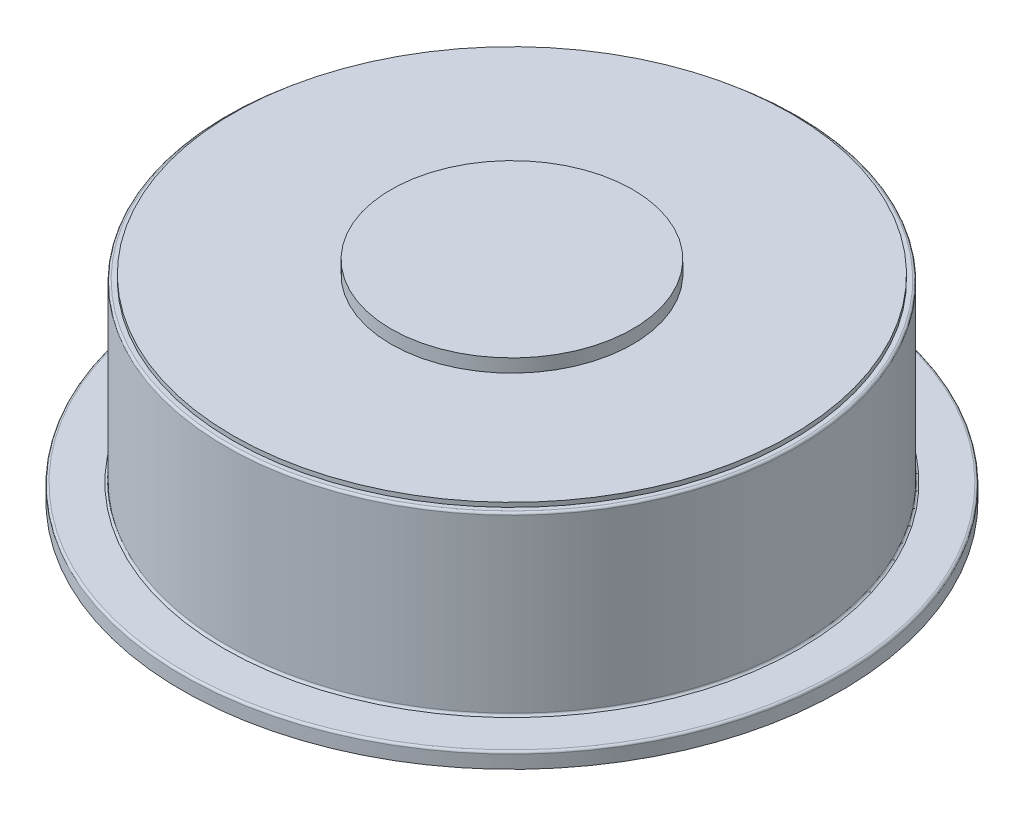
SolidWorks part; units mm, degrees
ref_plane "Ön Düzlem" through (0, 0, 0) normal (0, 0, 1) x (1, 0, 0)
ref_plane "Üst Düzlem" through (0, 0, 0) normal (0, 1, 0) x (1, 0, 0)
ref_plane "Sağ Düzlem" through (0, 0, 0) normal (1, 0, 0) x (0, 0, -1)
sketch "Çizim2" plane through (0, 0, 0) normal (0, 0, 1) x (1, 0, 0)
  line L1 (0, 0) -> (-150, 0)
  line L2 (0, 0) -> (0, 7)
  line L3 (0, 7) -> (-150, 7)
  line L4 (-150, 0) -> (-150, 7)
  line L5 (0, 7) -> (-130, 7)
  line L6 (0, 7) -> (0, 87)
  line L7 (0, 87) -> (-130, 87)
  line L8 (-130, 7) -> (-130, 87)
  dimension "D1" = 7
  dimension "D2" = 80
  dimension "D3" = 150
  dimension "D4" = 130
revolve "Döndür1" add sketch "Çizim2" angle 360 about L6
sketch "Çizim3" plane through (0, 87, 0) normal (0, 1, 0) x (1, 0, 0)
  circle A0 centre (0, 0) radius 127
  dimension "D1" = 254
extrude "Yükseklik-Ekstrüzyon1" add sketch "Çizim3" along normal blind 2
fillet "Radyus1" radius 1 2 edges at (0, 87, -130) (0, 7, -130)
fillet "Radyus2" radius 1 1 edges at (0, 7, -150)
sketch "Çizim5" plane through (0, 89, 0) normal (0, 1, 0) x (1, 0, 0)
  circle A0 centre (0, 0) radius 55
  dimension "D1" = 110
extrude "Yükseklik-Ekstrüzyon2" add sketch "Çizim5" along normal blind 6
